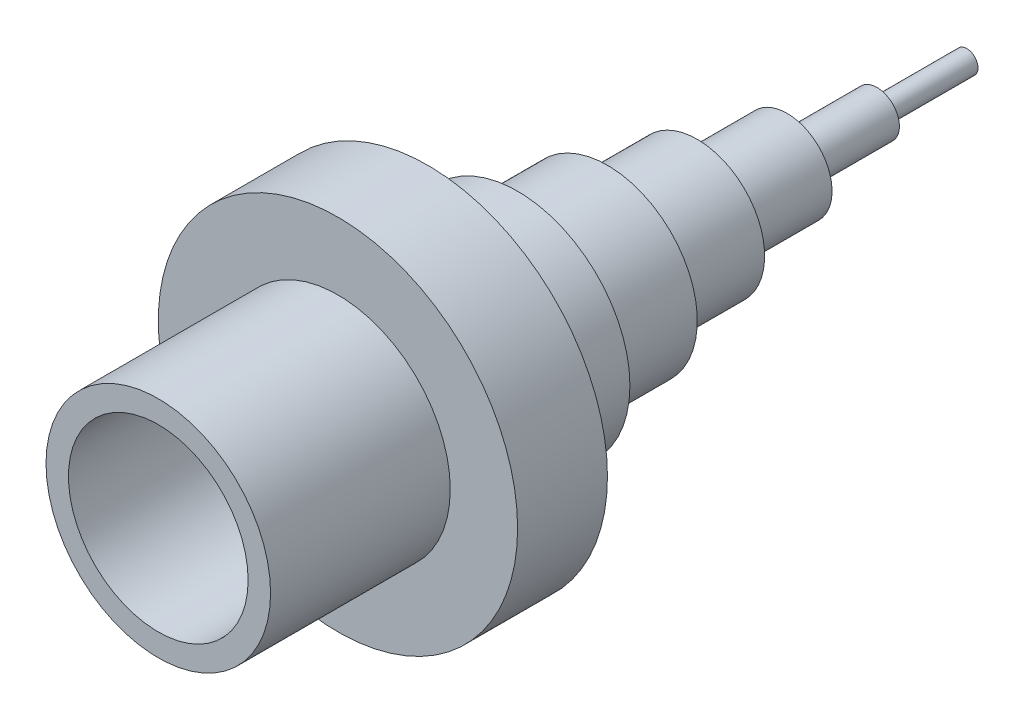
SolidWorks part; units mm, degrees
ref_plane "Front Plane" through (0, 0, 0) normal (0, 0, 1) x (1, 0, 0)
ref_plane "Top Plane" through (0, 0, 0) normal (0, 1, 0) x (1, 0, 0)
ref_plane "Right Plane" through (0, 0, 0) normal (1, 0, 0) x (0, 0, -1)
sketch "Sketch2" plane through (0, 0, 0) normal (0, 0, 1) x (1, 0, 0)
  circle A0 centre (0, 0) radius 1016
  dimension "D1" = 2032
extrude "Boss-Extrude1" add sketch "Sketch2" along normal blind 508
sketch "Sketch3" plane through (0, 0, 508) normal (0, 0, 1) x (1, 0, 0)
  circle A0 centre (0, 0) radius 635
  circle A1 centre (0, 0) radius 508
  dimension "D1" = 1270
  dimension "D2" = 1016
extrude "Boss-Extrude2" add sketch "Sketch3" along normal blind 1016
sketch "Sketch4" plane through (0, 0, 0) normal (0, 0, -1) x (-1, 0, 0)
  circle A0 centre (0, 0) radius 635
  dimension "D1" = 1270
extrude "Boss-Extrude3" add sketch "Sketch4" along normal blind 508
sketch "Sketch5" plane through (0, 0, -508) normal (0, 0, -1) x (-1, 0, 0)
  circle A0 centre (0, 0) radius 508
  dimension "D1" = 1016
extrude "Boss-Extrude4" add sketch "Sketch5" along normal blind 508
sketch "Sketch7" plane through (0, 0, -1016) normal (0, 0, -1) x (-1, 0, 0)
  circle A0 centre (0, 0) radius 381
  dimension "D1" = 762
extrude "Boss-Extrude5" add sketch "Sketch7" along normal blind 508 contours A0
sketch "Sketch8" plane through (0, 0, -1524) normal (0, 0, -1) x (-1, 0, 0)
  circle A0 centre (0, 0) radius 254
  dimension "D1" = 508
extrude "Boss-Extrude6" add sketch "Sketch8" along normal blind 508
sketch "Sketch9" plane through (0, 0, -2032) normal (0, 0, -1) x (-1, 0, 0)
  circle A0 centre (0, 0) radius 127
  dimension "D1" = 254
extrude "Boss-Extrude7" add sketch "Sketch9" along normal blind 508
sketch "Sketch10" plane through (0, 0, -2540) normal (0, 0, -1) x (-1, 0, 0)
  circle A0 centre (0, 0) radius 63.5
  dimension "D1" = 127
extrude "Boss-Extrude8" add sketch "Sketch10" along normal blind 508
